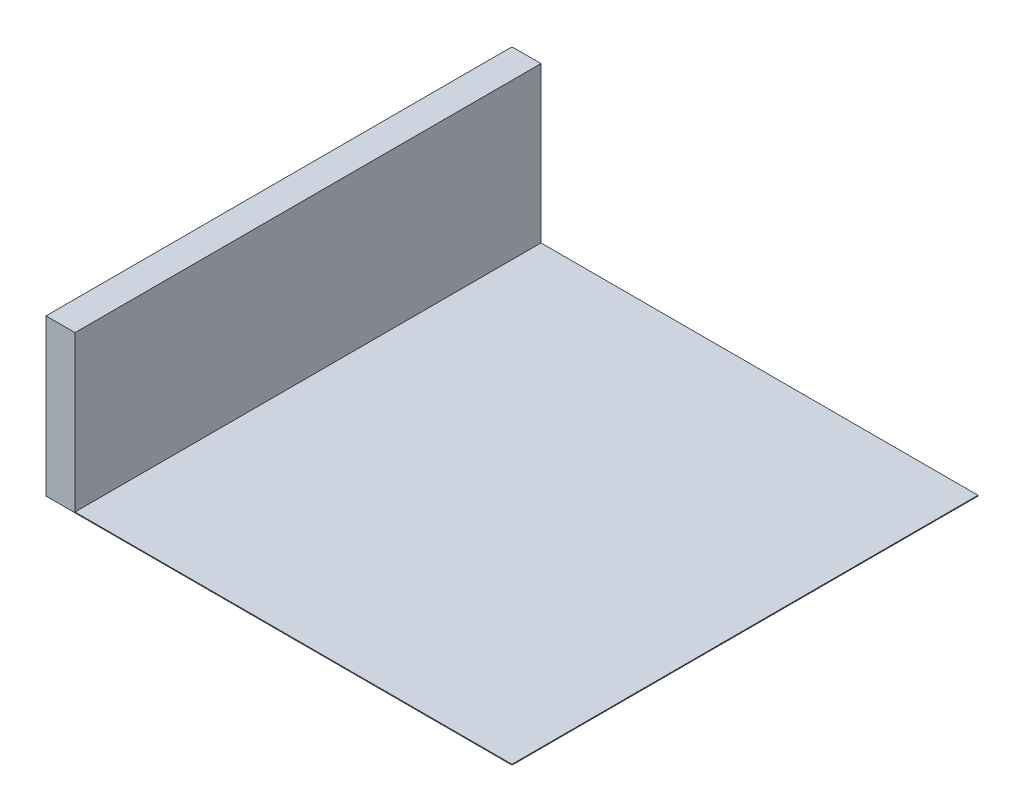
SolidWorks part; units mm, degrees
ref_plane "Front Plane" through (0, 0, 0) normal (0, 0, 1) x (1, 0, 0)
ref_plane "Top Plane" through (0, 0, 0) normal (0, 1, 0) x (1, 0, 0)
ref_plane "Right Plane" through (0, 0, 0) normal (1, 0, 0) x (0, 0, -1)
sketch "Sketch1" plane through (0, 0, 0) normal (0, 1, 0) x (1, 0, 0)
  line L1 (-127.1421, 934.4811) -> (1372.8579, 934.4811)
  line L2 (-127.1421, 934.4811) -> (-127.1421, -565.5189)
  line L3 (-127.1421, -565.5189) -> (1372.8579, -565.5189)
  line L4 (1372.8579, 934.4811) -> (1372.8579, -565.5189)
  point P4 (1372.8579, -617.709)
  dimension "D1" = 1500
  dimension "D2" = 1500
extrude "Boss-Extrude1" add sketch "Sketch1" along normal blind 2.54 contours L1 L4 L3 L2
sketch "Sketch2" plane through (0, 2.54, 0) normal (0, 1, 0) x (1, 0, 0)
  line L0 (-127.1421, -565.5189) -> (1372.8579, -565.5189) construction
  line L1 (-127.1421, 934.4811) -> (-33.7455, 934.4811)
  line L2 (-127.1421, 934.4811) -> (-127.1421, -565.5189)
  line L3 (-127.1421, -565.5189) -> (-33.7455, -565.5189)
  line L4 (-33.7455, 934.4811) -> (-33.7455, -565.5189)
extrude "Boss-Extrude2" add sketch "Sketch2" along normal blind 500
